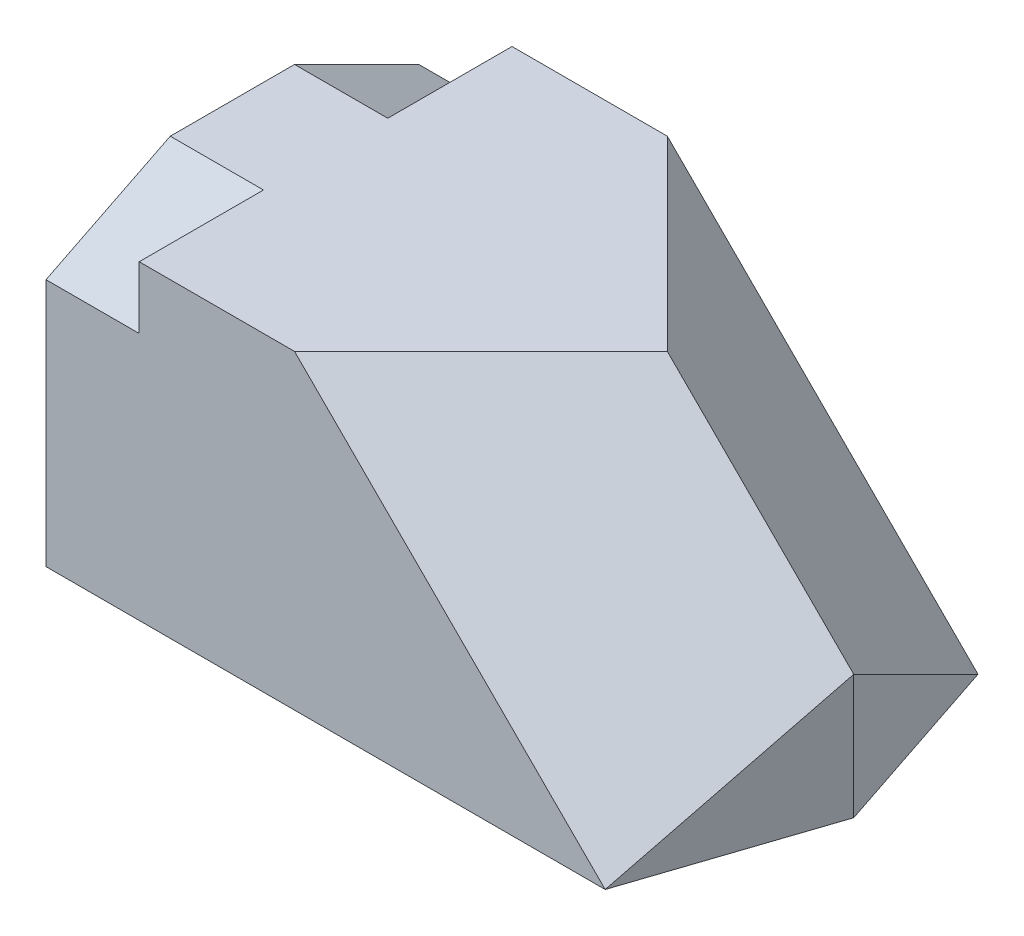
SolidWorks part; units mm, degrees
material "Alloy Steel"
ref_plane "정면" through (0, 0, 0) normal (0, 0, 1) x (1, 0, 0)
ref_plane "윗면" through (0, 0, 0) normal (0, 1, 0) x (1, 0, 0)
ref_plane "우측면" through (0, 0, 0) normal (1, 0, 0) x (0, 0, -1)
sketch "스케치2" plane through (0, 0, 0) normal (0, 0, 1) x (1, 0, 0)
  line L0 (0, 0) -> (100, 0) construction
  line L1 (0, 0) -> (100, 0)
  line L2 (0, 0) -> (0, 50)
  line L3 (0, 50) -> (100, 50)
  line L4 (100, 0) -> (100, 50)
  dimension "D1" = 100
  dimension "D2" = 50
extrude "보스-돌출1" add sketch "스케치2" along normal mid plane 60
sketch "스케치7" plane through (0, 50, 0) normal (0, 1, 0) x (1, 0, 0)
  line L0 (0, 0) -> (100, 0) construction
  line L1 (100, -30) -> (100, 30) construction
  line L2 (15, -30) -> (15, 30)
  line L3 (100, 30) -> (0, 30) construction
  line L4 (15, 30) -> (40, 30)
  line L5 (40, 30) -> (70, 0)
  line L6 (15, -30) -> (40, -30)
  line L7 (40, -30) -> (70, 0)
  point P5 (0, 0)
  point P13 (15, 0)
  line M6 (100, 30) -> (0, 30)
  line M8 (0, -30) -> (100, -30)
  line M9 (100, -30) -> (100, 30)
  dimension "D1" = 15
  dimension "D2" = 25
  dimension "D3" = 30
sketch "스케치8" plane through (0, 0, 0) normal (0, 0, 1) x (1, 0, 0)
  line L0 (70, 50) -> (100, 20)
  line L1 (100, 0) -> (100, 50) construction
  line L2 (0, 0) -> (100, 0) construction
  point P7 (0, 0)
  dimension "D1" = 20
extrude "컷-돌출1" cut sketch "스케치7" along direction (0.7071, -0.7071, 0) on the side against the normal through all contours L0 L7 M8 M9 | L5 L0 M9 M6
ref_plane "평면1" through (90, 0, 30) normal (-0.9487, 0, -0.3162) x (-0.3162, 0, 0.9487)
sketch "스케치10" plane through (90, 0, 30) normal (-0.9487, 0, -0.3162) x (-0.3162, 0, 0.9487)
  line L0 (-31.6228, 20) -> (-31.6228, 0)
  line L1 (-31.6228, 0) -> (0, 0)
  line L2 (0, 0) -> (-31.6228, 20)
extrude "컷-돌출2" cut sketch "스케치10" against normal through all
mirror "대칭 복사1" about plane through (0, 0, 0) normal (0, 0, 1) of "컷-돌출2"
sketch "스케치11" plane through (0, 0, 0) normal (-1, 0, 0) x (0, 0, 1)
  line L0 (0, 0) -> (0, 50) construction
  line L1 (30, 50) -> (-30, 50) construction
  line L2 (-30, 40) -> (-10, 50)
  line L3 (-30, 50) -> (-30, 0) construction
  line L4 (30, 40) -> (10, 50)
  line L5 (-10, 50) -> (-30, 50)
  line L6 (10, 50) -> (30, 50)
  line L7 (-30, 50) -> (-30, 40)
  line L8 (30, 50) -> (30, 40)
  point P14 (-16.6796, 50)
  dimension "D1" = 20
  dimension "D2" = 10
extrude "컷-돌출4" cut sketch "스케치11" against normal blind 15
